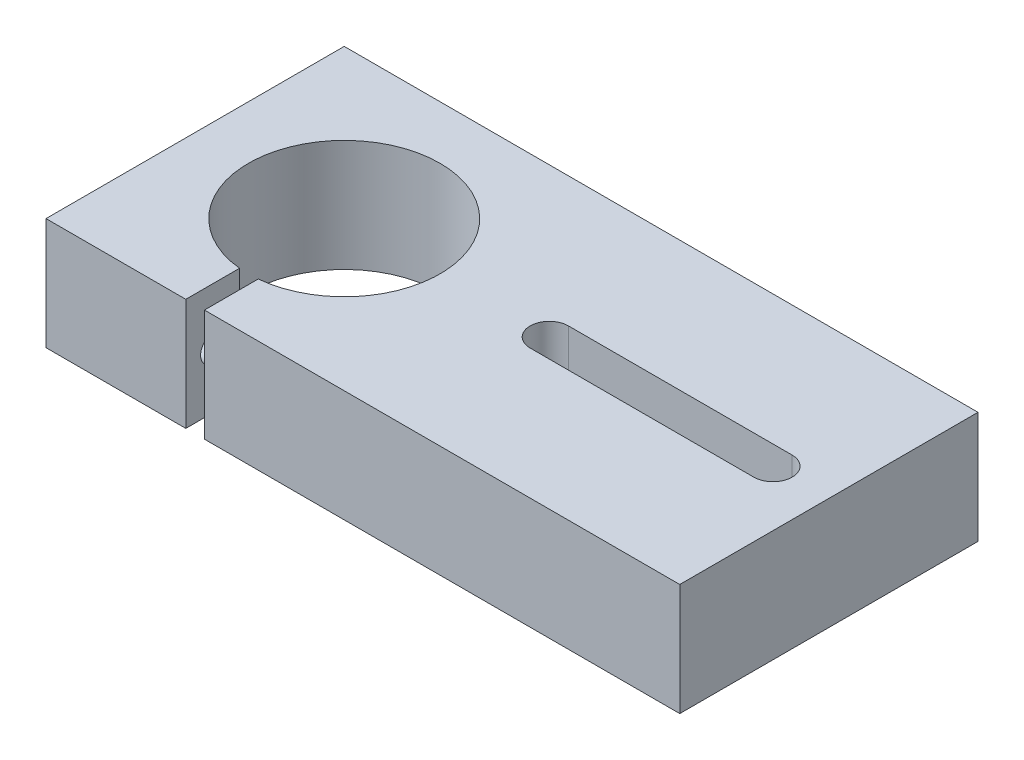
SolidWorks part; units mm, degrees
ref_plane "Front" through (0, 0, 0) normal (0, 0, 1) x (1, 0, 0)
ref_plane "Top" through (0, 0, 0) normal (0, 1, 0) x (1, 0, 0)
ref_plane "Right" through (0, 0, 0) normal (1, 0, 0) x (0, 0, -1)
sketch "Sketch1" plane through (0, 0, 0) normal (0, 1, 0) x (1, 0, 0)
  line L1 (-53.975, -25.4) -> (53.975, -25.4)
  line L2 (-53.975, -25.4) -> (-53.975, 25.4)
  line L3 (-53.975, 25.4) -> (53.975, 25.4)
  line L4 (53.975, -25.4) -> (53.975, 25.4)
  line L5 (-53.975, -25.4) -> (53.975, 25.4) construction
  line L6 (-53.975, 25.4) -> (53.975, -25.4) construction
  point P0 (0, 0)
  dimension "D1" = 50.8
  dimension "D2" = 107.95
extrude "Boss-Extrude1" add sketch "Sketch1" along normal mid plane 19.05 contours L3 L4 L1 L2
sketch "Sketch2" plane through (0, 9.525, 0) normal (0, 1, 0) x (1, 0, 0)
  line L0 (-50, 0) -> (50, 0) construction
  line L1 (-53.975, -25.4) -> (-53.975, 25.4) construction
  circle A0 centre (-28.575, 0) radius 16.3195
  dimension "D1" = 32.639
  dimension "D2" = 25.4
extrude "Cut-Extrude1" cut sketch "Sketch2" against normal blind 19.05 contours A0
sketch "Sketch3" plane through (0, 9.525, 0) normal (0, 1, 0) x (1, 0, 0)
  line L0 (-50, 0) -> (50, 0) construction
  line L1 (-30.1625, -25.4) -> (-26.9875, -25.4)
  line L2 (-30.1625, -25.4) -> (-30.1625, 0)
  line L3 (-30.1625, 0) -> (-26.9875, 0)
  line L4 (-26.9875, -25.4) -> (-26.9875, 0)
  line L5 (-30.1625, -25.4) -> (-26.9875, 0) construction
  line L6 (-30.1625, 0) -> (-26.9875, -25.4) construction
  line L7 (-53.975, -25.4) -> (53.975, -25.4) construction
  point P0 (-28.575, -12.7)
  point P7 (-28.575, 0)
  point P8 (-28.575, 0)
  dimension "D1" = 3.175
extrude "Cut-Extrude2" cut sketch "Sketch3" against normal blind 19.05
sketch "Sketch4" plane through (-53.975, 0, 0) normal (-1, 0, 0) x (0, 0, 1)
  line L0 (50, 0) -> (-50, 0) construction
  line L1 (25.4, 9.525) -> (25.4, -9.525) construction
  point P0 (20.6375, 0)
  dimension "D1" = 4.7625
hole_wizard "CBORE for #8 Socket Head Cap Screw1" positions "Sketch5" profile "Sketch7" counterbore size "#8" standard "ANSI Inch"
sketch "Sketch5" plane through (-53.975, 0, 0) normal (-1, 0, 0) x (0, 0, 1)
  point P0 (20.6375, 0)
sketch "Sketch7" plane through (-53.975, 0, 20.6375) normal (0, 1, 0) x (0, 0, 1)
  line L0 (0, 0) -> (0, 23.8125)
  line L1 (0, 23.8125) -> (2.2479, 23.8125)
  line L3 (2.2479, 23.8125) -> (2.2479, 4.1656)
  line L4 (2.2479, 4.1656) -> (3.9687, 4.1656)
  line L5 (3.9687, 4.1656) -> (3.9687, 0)
  line L7 (3.9687, 0) -> (0, 0)
  line L11 (0, -6.35) -> (0, 107.95) construction
  dimension "Thru Hole Dia." = 4.4958
  dimension "Thru Hole Depth" = 23.8125
  dimension "C'Bore Dia." = 7.9375
  dimension "C'Bore Depth" = 4.1656
hole_wizard "#8-32 Tapped Hole1" positions "Sketch10" profile "Sketch11" tap size "#8-32" standard "ANSI Inch"
sketch "Sketch10" plane through (-26.9875, 0, 0) normal (-1, 0, 0) x (0, 0, 1)
  point P0 (20.6375, 0)
sketch "Sketch11" plane through (-26.9875, 0, 20.6375) normal (0, 1, 0) x (0, 0, 1)
  line L0 (0, 0) -> (0, 26.4378)
  line L1 (0, 26.4378) -> (1.7272, 25.4)
  line L2 (1.7272, 25.4) -> (1.7272, 0)
  line L5 (1.7272, 0) -> (0, 0)
  line L10 (0, 26.4378) -> (-1.7272, 25.4) construction
  line L11 (0, -6.35) -> (0, 107.95) construction
  dimension "Tap Drill Dia." = 3.4544
  dimension "Tap Drill Depth" = 25.4
  dimension "Drill Angle" = 118
cosmetic thread "Hole Thread1" parameters "D1"=8.382, "D2"=4.1656
sketch "Sketch12" plane through (0, 9.525, 0) normal (0, 1, 0) x (1, 0, 0)
  line L0 (6.35, 0) -> (44.45, 0) construction
  line L1 (-50, 0) -> (50, 0) construction
  line L2 (6.35, 3.2639) -> (44.45, 3.2639)
  line L3 (6.35, -3.2639) -> (44.45, -3.2639)
  line L4 (53.975, -25.4) -> (53.975, 25.4) construction
  arc A0 (6.35, 3.2639) -> (6.35, -3.2639) centre (6.35, 0) ccw
  arc A1 (44.45, -3.2639) -> (44.45, 3.2639) centre (44.45, 0) ccw
  point P5 (25.4, 0)
  dimension "D1" = 6.5278
  dimension "D2" = 38.1
  dimension "D3" = 28.575
extrude "Cut-Extrude3" cut sketch "Sketch12" against normal blind 19.05
